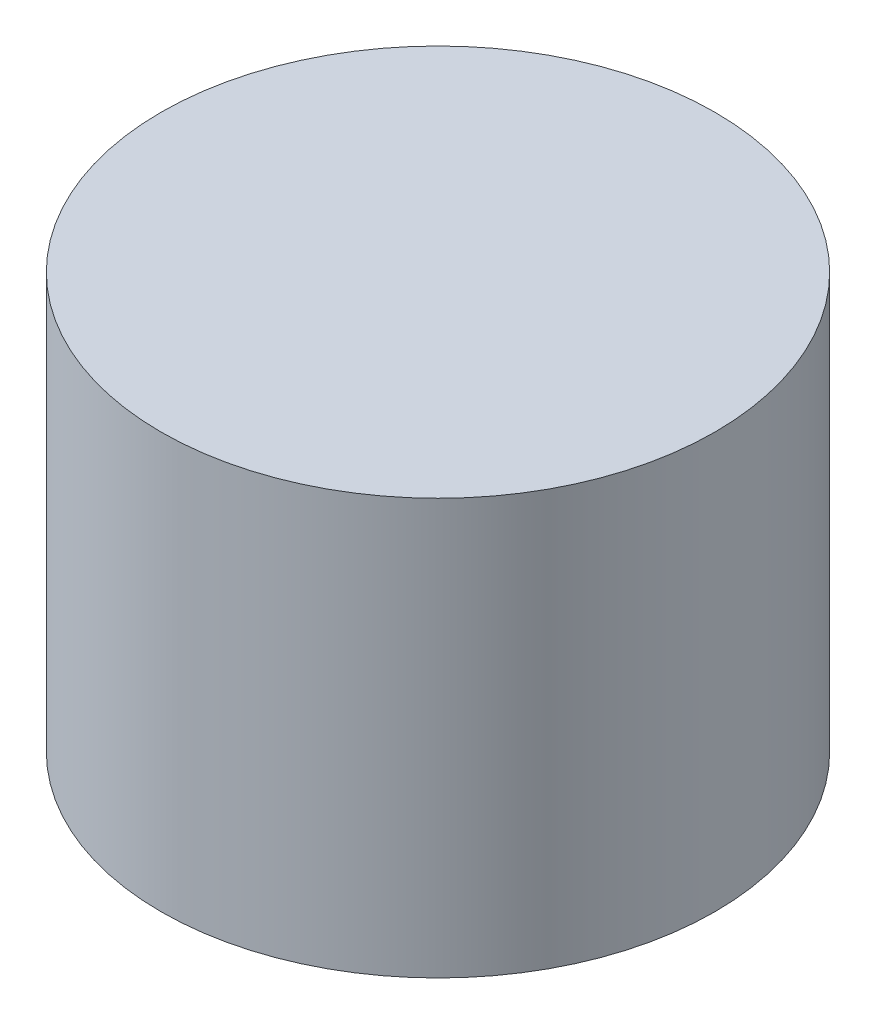
SolidWorks part; units mm, degrees
ref_plane "Front Plane" through (0, 0, 0) normal (0, 0, 1) x (1, 0, 0)
ref_plane "Top Plane" through (0, 0, 0) normal (0, 1, 0) x (1, 0, 0)
ref_plane "Right Plane" through (0, 0, 0) normal (1, 0, 0) x (0, 0, -1)
other "Configuration Table"
sketch "Sketch1" plane through (0, 0, 0) normal (0, 1, 0) x (1, 0, 0)
  circle A0 centre (500, 300) radius 60
extrude "OVEN_egzoz_fani_D120" add sketch "Sketch1" along normal blind 90 from offset 1700 separate body
